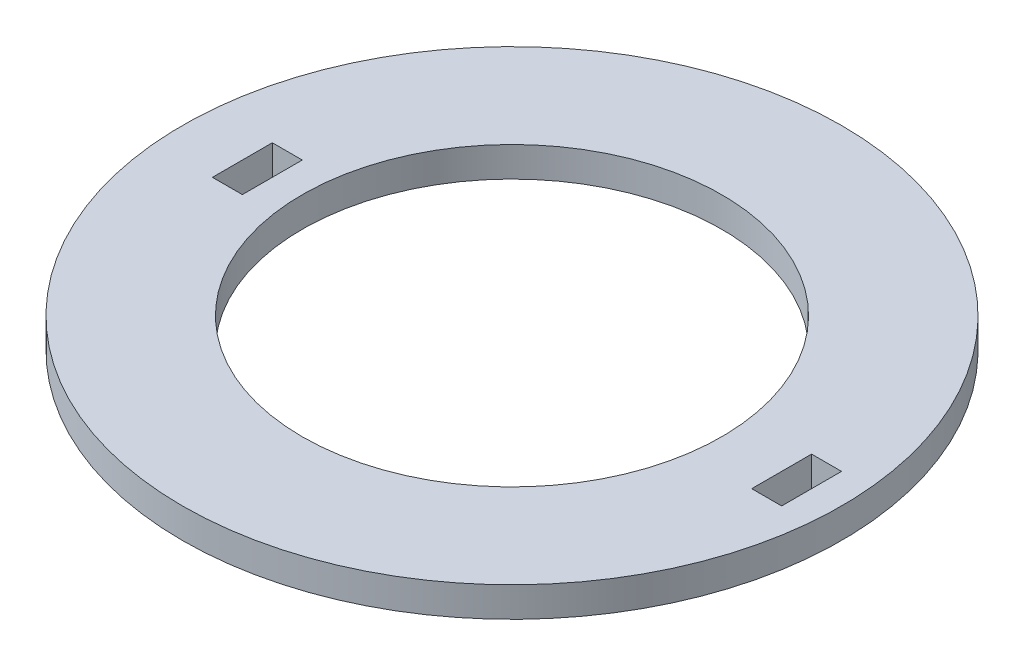
SolidWorks part; units mm, degrees
ref_plane "Front Plane" through (0, 0, 0) normal (0, 0, 1) x (1, 0, 0)
ref_plane "Top Plane" through (0, 0, 0) normal (0, 1, 0) x (1, 0, 0)
ref_plane "Right Plane" through (0, 0, 0) normal (1, 0, 0) x (0, 0, -1)
sketch "Sketch1" plane through (0, 0, 0) normal (0, 1, 0) x (1, 0, 0)
  circle A0 centre (0, 0) radius 35
  circle A1 centre (0, 0) radius 55
  dimension "D1" = 110
  dimension "D2" = 70
extrude "Boss-Extrude1" add sketch "Sketch1" along normal blind 5
sketch "Sketch2" plane through (0, 5, 0) normal (0, 1, 0) x (1, 0, 0)
  line L1 (-45, -5) -> (-40, -5)
  line L2 (-45, -5) -> (-45, 5)
  line L3 (-45, 5) -> (-40, 5)
  line L4 (-40, -5) -> (-40, 5)
  line L5 (-45, -5) -> (-40, 5) construction
  line L6 (-45, 5) -> (-40, -5) construction
  line L12 (45, -5) -> (50, -5)
  line L13 (45, -5) -> (45, 5)
  line L14 (45, 5) -> (50, 5)
  line L15 (50, -5) -> (50, 5)
  line L16 (45, -5) -> (50, 5) construction
  line L17 (45, 5) -> (50, -5) construction
  point P0 (-42.5, 0)
  point P5 (47.5, 0)
  dimension "D1" = 10
  dimension "D2" = 5
  dimension "D3" = 40
  dimension "D4" = 5
  dimension "D5" = 10
  dimension "D6" = 45
extrude "Cut-Extrude1" cut sketch "Sketch2" against normal blind 5
